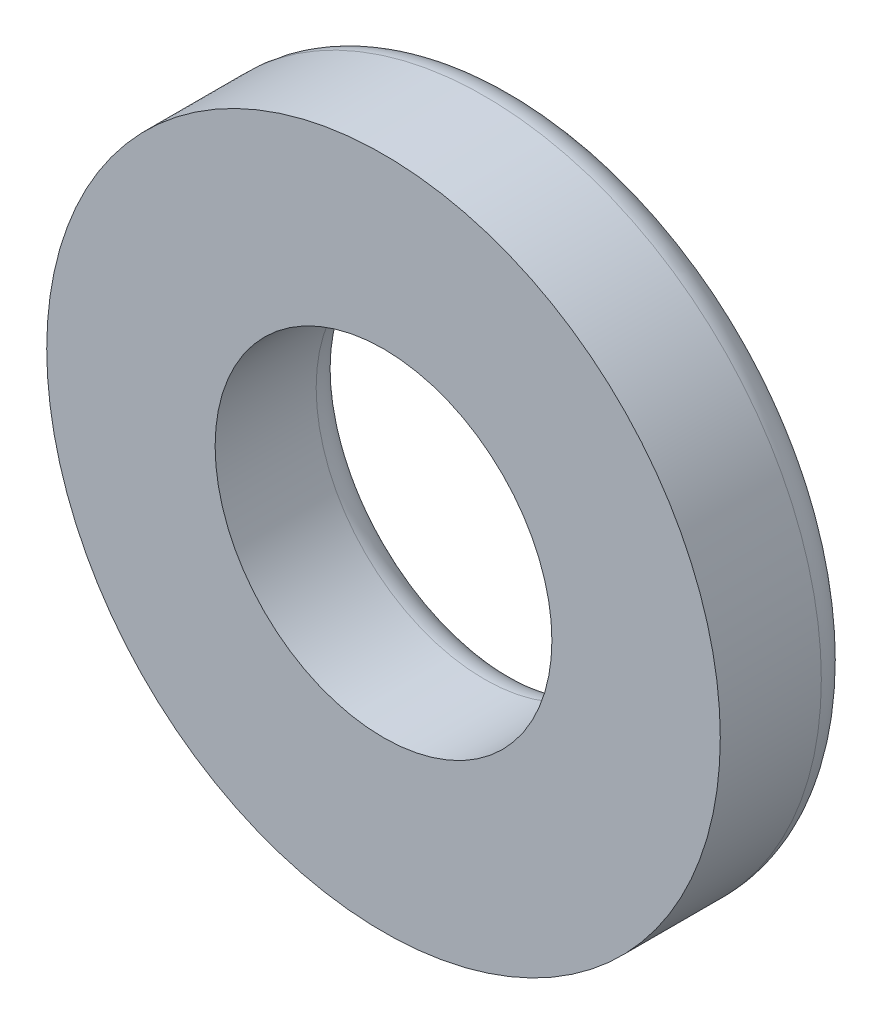
SolidWorks part; units mm, degrees
material "1.0037 (S235JR)"
ref_plane "Front Plane" through (0, 0, 0) normal (0, 0, 1) x (1, 0, 0)
ref_plane "Top Plane" through (0, 0, 0) normal (0, 1, 0) x (1, 0, 0)
ref_plane "Right Plane" through (0, 0, 0) normal (1, 0, 0) x (0, 0, -1)
sketch "Sketch1" plane through (0, 0, 0) normal (0, 0, 1) x (1, 0, 0)
  circle A0 centre (0, 0) radius 15
  circle A1 centre (0, 0) radius 30
  dimension "D1" = 60
  dimension "D2" = 30
extrude "Boss-Extrude1" add sketch "Sketch1" along normal blind 12
fillet "Fillet1" radius 3 2 edges at (15, 0, 0) (30, 0, 0)
